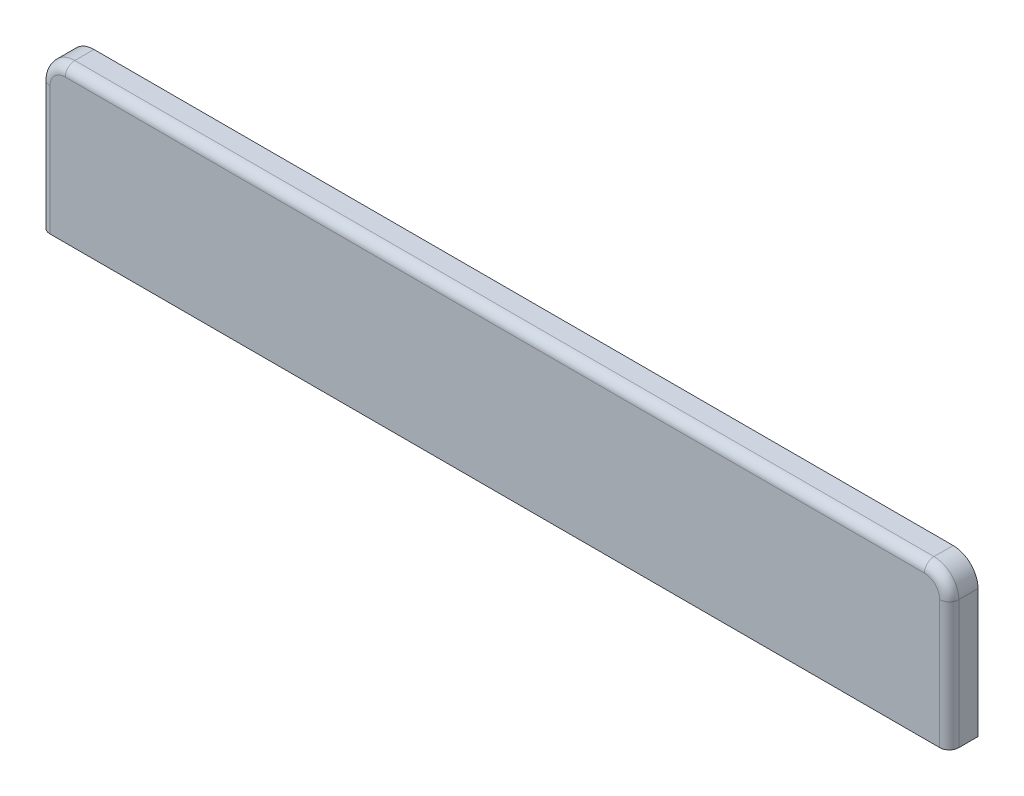
SolidWorks part; units mm, degrees
ref_plane "Front" through (0, 0, 0) normal (0, 0, 1) x (1, 0, 0)
ref_plane "Top" through (0, 0, 0) normal (0, 1, 0) x (1, 0, 0)
ref_plane "Right" through (0, 0, 0) normal (1, 0, 0) x (0, 0, -1)
sketch "Sketch1" plane through (0, 0, 0) normal (0, 0, 1) x (1, 0, 0)
  line L0 (301.625, 101.6) -> (301.625, 0)
  line L1 (301.625, 101.6) -> (-301.625, 101.6)
  line L2 (301.625, 0) -> (-301.625, 0)
  line L3 (-301.625, 101.6) -> (-301.625, 0)
  line L4 (301.625, 101.6) -> (-301.625, 0) construction
  line L5 (301.625, 0) -> (-301.625, 101.6) construction
  line L6 (0, 50.8) -> (0, 0) construction
  point P1 (0, 50.8)
  dimension "D1" = 101.6
  dimension "D2" = 603.25
extrude "Boss-Extrude1" add sketch "Sketch1" along normal blind 19.05
fillet "Fillet1" radius 16.51 2 edges at (-301.625, 101.6, 9.525) (301.625, 101.6, 9.525)
fillet "Fillet2" radius 6.35 5 edges at (301.625, 42.545, 19.05) (296.7893, 96.7643, 19.05) (0, 101.6, 19.05) (-296.7893, 96.7643, 19.05) (-301.625, 42.545, 19.05)
